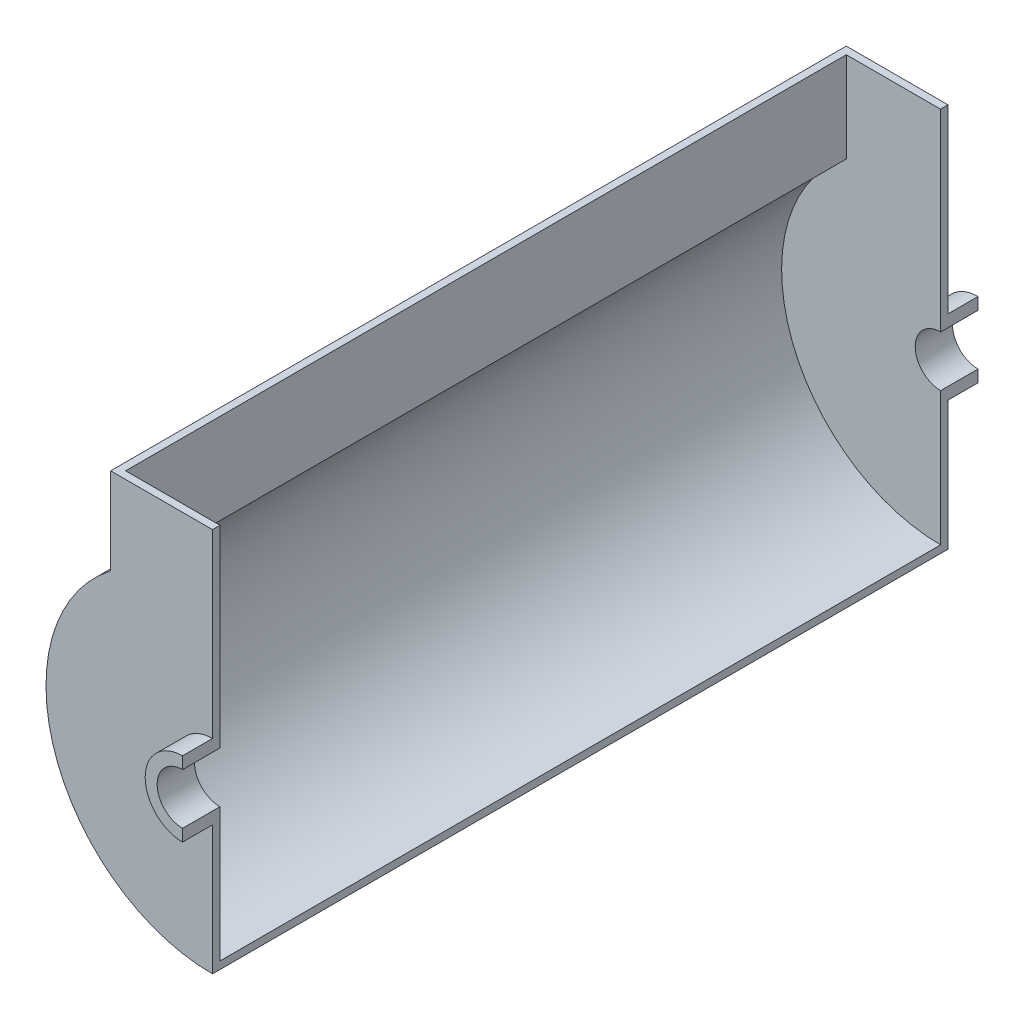
SolidWorks part; units mm, degrees
ref_plane "Front Plane" through (0, 0, 0) normal (0, 0, 1) x (1, 0, 0)
ref_plane "Top Plane" through (0, 0, 0) normal (0, 1, 0) x (1, 0, 0)
ref_plane "Right Plane" through (0, 0, 0) normal (1, 0, 0) x (0, 0, -1)
sketch "Sketch1" plane through (0, 0, 0) normal (0, 0, 1) x (1, 0, 0)
  line L0 (0, 25) -> (0, 17)
  line L1 (0, -17) -> (0, -25)
  arc A0 (0, 17) -> (0, -17) centre (0, 0) ccw
  arc A1 (0, 25) -> (0, -25) centre (0, 0) ccw
  dimension "D1" = 50
  dimension "D2" = 34
extrude "Boss-Extrude1" add sketch "Sketch1" along normal blind 20 and the other way blind 5
sketch "Sketch2" plane through (0, 0, 0) normal (0, 0, 1) x (1, 0, 0)
  line L0 (0, 25) -> (0, 146.0148)
  line L1 (0, 146.0148) -> (-68.0936, 146.0148)
  line L2 (-68.0936, 146.0148) -> (-68.0936, 88.0879)
  line L3 (0, -25) -> (0, -111.3383)
  arc A0 (0, 25) -> (0, -25) centre (0, 0) ccw construction
  arc A1 (0, 25) -> (0, -25) centre (0, 0) ccw
  arc A2 (-68.0936, 88.0879) -> (0, -111.3383) centre (0, 0) ccw
extrude "Boss-Extrude2" add sketch "Sketch2" against normal blind 5
ref_plane "Plane1" through (0, 0, -246) normal (0, 0, 1) x (1, 0, 0)
mirror "Mirror2" about plane through (0, 0, -246) normal (0, 0, 1) of bodies 102
sketch "Sketch3" plane through (0, 0, -5) normal (0, 0, -1) x (-1, 0, 0)
  line L1 (68.0936, 146.0148) -> (68.0936, 88.0879) construction
  line L2 (68.0936, 146.0148) -> (68.0936, 88.0879)
  line L3 (63.0936, 146.0148) -> (63.0936, 85.5981)
  line L4 (68.0936, 146.0148) -> (63.0936, 146.0148)
  line L5 (0, -111.3383) -> (0, -106.3383)
  arc A0 (0, -111.3383) -> (68.0936, 88.0879) centre (0, 0) ccw construction
  arc A1 (0, -111.3383) -> (68.0936, 88.0879) centre (0, 0) ccw
  arc A2 (0, -106.3383) -> (63.0936, 85.5981) centre (0, 0) ccw
  dimension "D1" = 5
extrude "Boss-Extrude3" add sketch "Sketch3" along normal up to surface (482 mm away)
